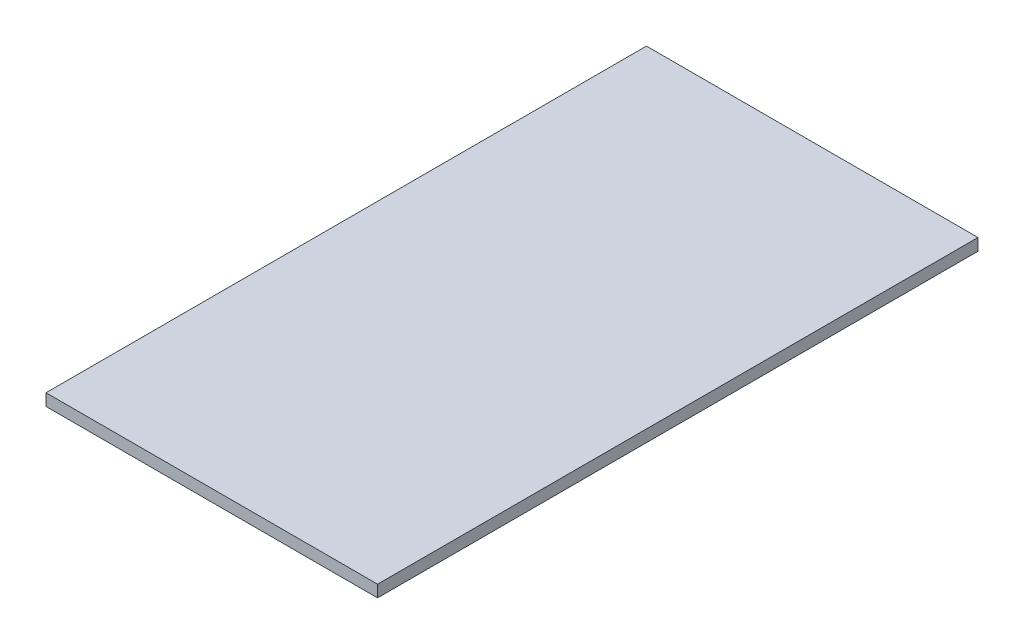
SolidWorks part; units mm, degrees
ref_plane "Front Plane" through (0, 0, 0) normal (0, 0, 1) x (1, 0, 0)
ref_plane "Top Plane" through (0, 0, 0) normal (0, 1, 0) x (1, 0, 0)
ref_plane "Right Plane" through (0, 0, 0) normal (1, 0, 0) x (0, 0, -1)
sketch "Sketch1" plane through (0, 0, 0) normal (0, 1, 0) x (1, 0, 0)
  line L1 (0, 0) -> (88.35, 0)
  line L2 (0, 0) -> (0, 160)
  line L3 (0, 160) -> (88.35, 160)
  line L4 (88.35, 0) -> (88.35, 160)
  dimension "D1" = 160
  dimension "D2" = 88.35
extrude "Boss-Extrude1" add sketch "Sketch1" along normal blind 3.175
